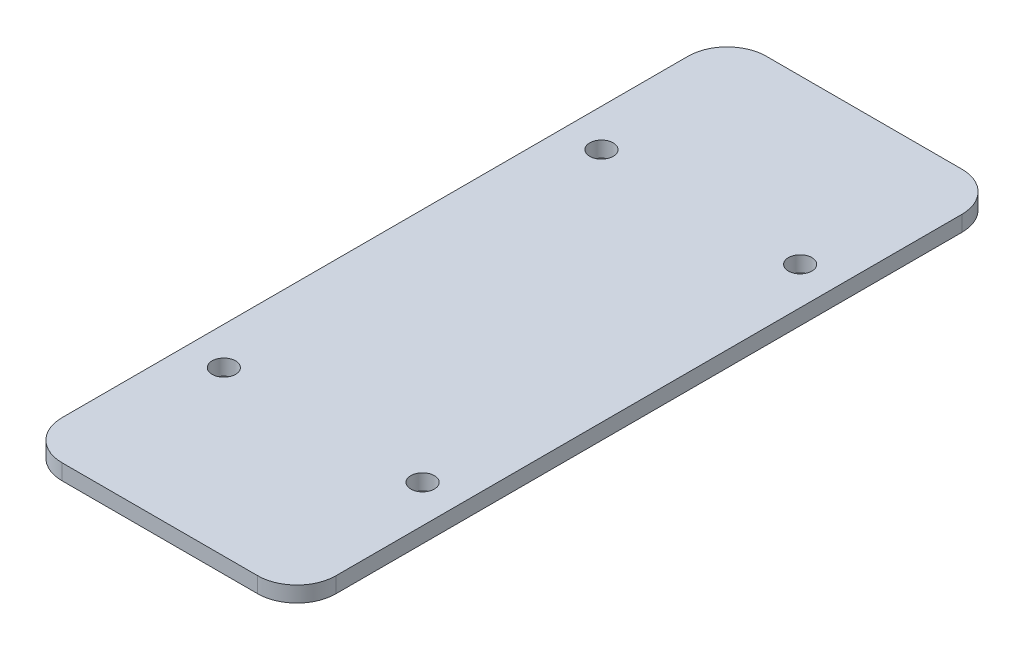
SolidWorks part; units mm, degrees
ref_plane "前视基准面" through (0, 0, 0) normal (0, 0, 1) x (1, 0, 0)
ref_plane "上视基准面" through (0, 0, 0) normal (0, 1, 0) x (1, 0, 0)
ref_plane "右视基准面" through (0, 0, 0) normal (1, 0, 0) x (0, 0, -1)
other "Configuration Table"
sketch "草图1" plane through (0, 0, 0) normal (0, 1, 0) x (1, 0, 0)
  line L1 (-17.5, -45) -> (17.5, -45)
  line L2 (-17.5, -45) -> (-17.5, 45)
  line L3 (-17.5, 45) -> (17.5, 45)
  line L4 (17.5, -45) -> (17.5, 45)
  line L5 (-17.5, -45) -> (17.5, 45) construction
  line L6 (-17.5, 45) -> (17.5, -45) construction
  point P0 (0, 0)
  dimension "D1" = 35
  dimension "D2" = 90
extrude "凸台-拉伸1" add sketch "草图1" along normal blind 2
sketch "草图2" plane through (0, 2, 0) normal (0, 1, 0) x (1, 0, 0)
  line L1 (-12.7, -24.13) -> (12.7, -24.13) construction
  line L2 (-12.7, -24.13) -> (-12.7, 24.13) construction
  line L3 (-12.7, 24.13) -> (12.7, 24.13) construction
  line L4 (12.7, -24.13) -> (12.7, 24.13) construction
  line L5 (-12.7, -24.13) -> (12.7, 24.13) construction
  line L6 (-12.7, 24.13) -> (12.7, -24.13) construction
  circle A0 centre (-12.7, 24.13) radius 1.5
  circle A1 centre (12.7, 24.13) radius 1.5
  circle A2 centre (12.7, -24.13) radius 1.5
  circle A3 centre (-12.7, -24.13) radius 1.5
  point P0 (0, 0)
  dimension "D3" = 3
  dimension "D4" = 3
  dimension "D5" = 3
  dimension "D6" = 3
  dimension "D1" = 25.4
  dimension "D2" = 48.26
extrude "切除-拉伸1" cut sketch "草图2" against normal through all
fillet "圆角1" radius 5 4 edges at (-17.5, 1, 45) (17.5, 1, 45) (17.5, 1, -45) (-17.5, 1, -45)
